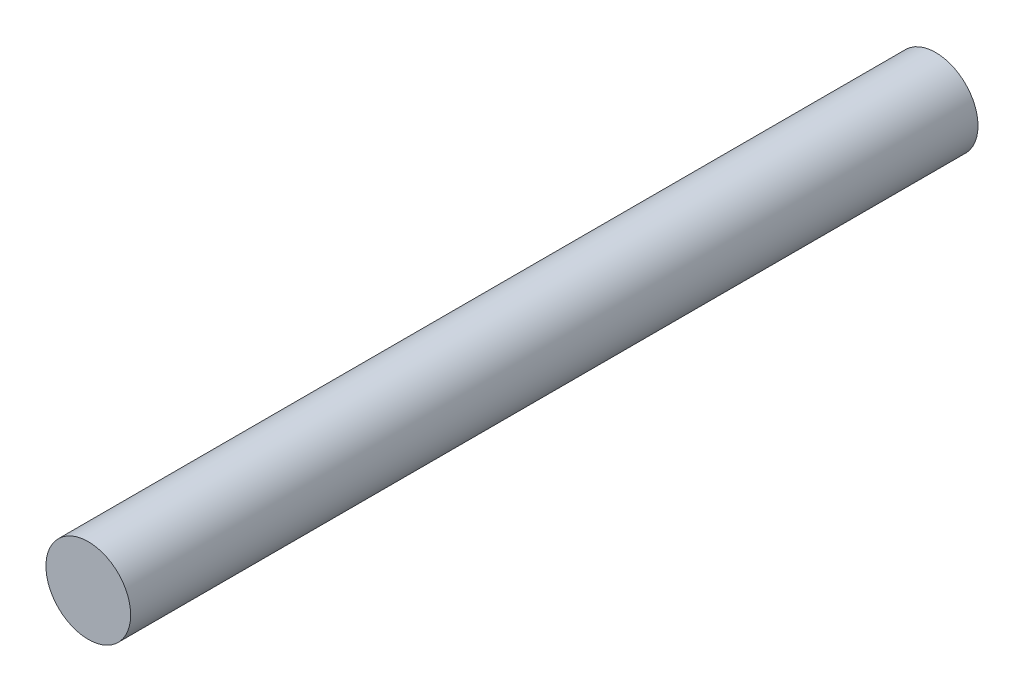
SolidWorks part; units mm, degrees
ref_plane "Front Plane" through (0, 0, 0) normal (0, 0, 1) x (1, 0, 0)
ref_plane "Top Plane" through (0, 0, 0) normal (0, 1, 0) x (1, 0, 0)
ref_plane "Right Plane" through (0, 0, 0) normal (1, 0, 0) x (0, 0, -1)
sketch "Sketch1" plane through (0, 0, 0) normal (0, 0, 1) x (1, 0, 0)
  circle A0 centre (0, 0) radius 2.5
extrude "Boss-Extrude1" add sketch "Sketch1" along normal blind 50
